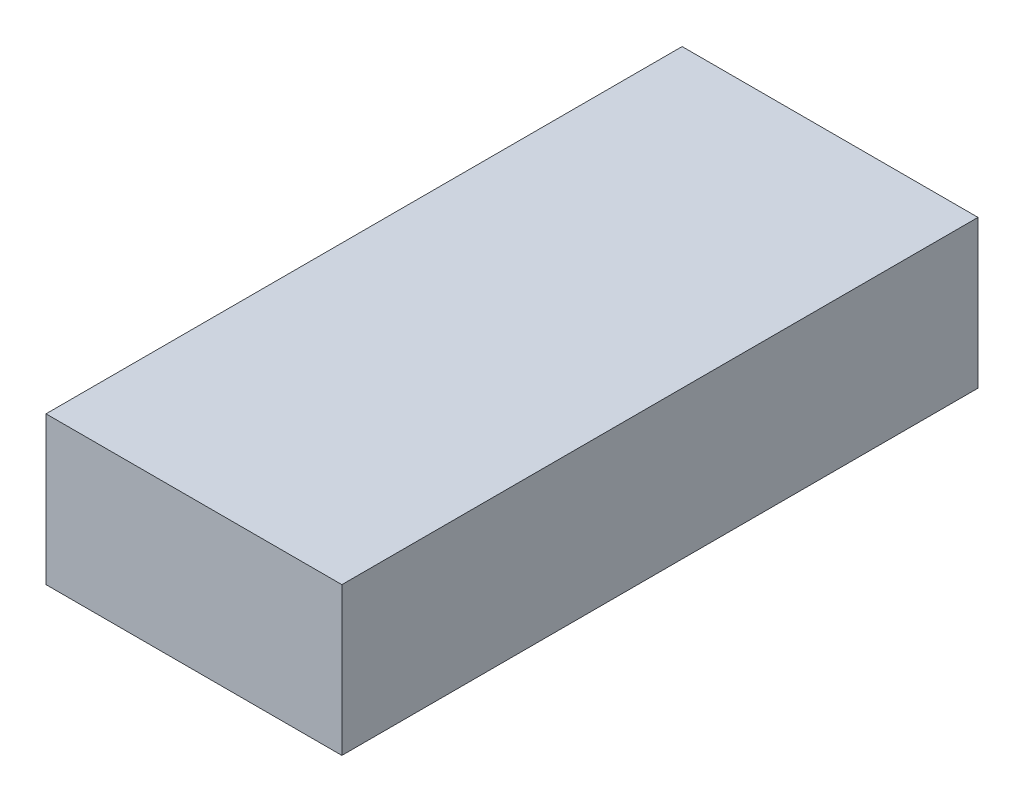
SolidWorks part; units mm, degrees
ref_plane "前视基准面" through (0, 0, 0) normal (0, 0, 1) x (1, 0, 0)
ref_plane "上视基准面" through (0, 0, 0) normal (0, 1, 0) x (1, 0, 0)
ref_plane "右视基准面" through (0, 0, 0) normal (1, 0, 0) x (0, 0, -1)
sketch "草图1" plane through (0, 0, 0) normal (0, 1, 0) x (1, 0, 0)
  line L1 (-10, 21.5) -> (10, 21.5)
  line L2 (-10, 21.5) -> (-10, -21.5)
  line L3 (-10, -21.5) -> (10, -21.5)
  line L4 (10, 21.5) -> (10, -21.5)
  line L5 (-10, 21.5) -> (10, -21.5) construction
  line L6 (-10, -21.5) -> (10, 21.5) construction
  point P0 (0, 0)
  dimension "D1" = 20
  dimension "D2" = 43
extrude "凸台-拉伸1" add sketch "草图1" along normal blind 10
